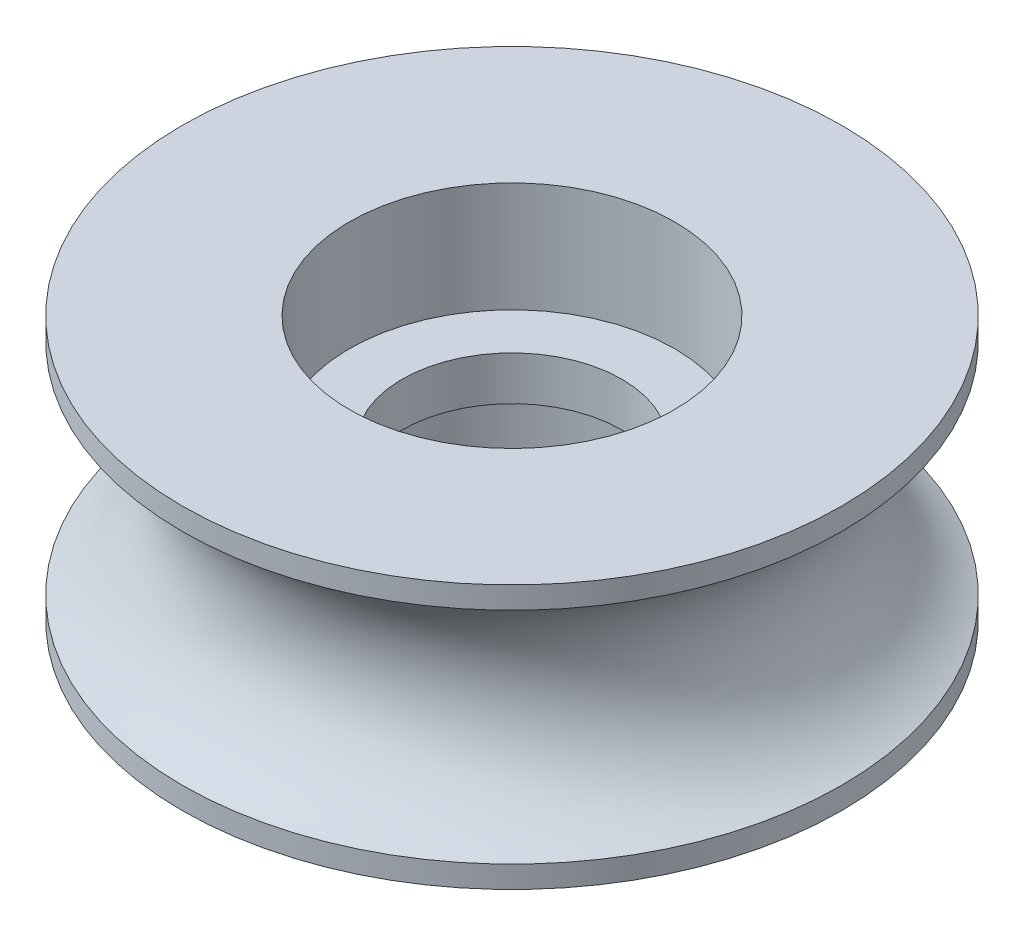
SolidWorks part; units mm, degrees
ref_plane "Ebene vorne" through (0, 0, 0) normal (0, 0, 1) x (1, 0, 0)
ref_plane "Ebene oben" through (0, 0, 0) normal (0, 1, 0) x (1, 0, 0)
ref_plane "Ebene rechts" through (0, 0, 0) normal (1, 0, 0) x (0, 0, -1)
sketch "Sketch1" plane through (0, 0, 0) normal (0, 0, 1) x (1, 0, 0)
  line L0 (0, -6.6295) -> (0, 11.8219) construction
  line L1 (-3.7, 0) -> (-7.5, 0)
  line L2 (-7.5, 0) -> (-7.5, 0.5)
  line L3 (-7.5, 6) -> (-3.7, 6)
  line L4 (-3.7, 6) -> (-3.7, 3.5)
  line L5 (-3.7, 2.5) -> (-3.7, 0)
  line L7 (-7.5, 5.5) -> (-7.5, 6)
  line L8 (-9.5865, 3) -> (-0.4874, 3) construction
  line L10 (-3.7, 2.5) -> (-2.5, 2.5)
  line L11 (-2.5, 2.5) -> (-2.5, 3.5)
  line L12 (-2.5, 3.5) -> (-3.7, 3.5)
  arc A1 (-7.5, 5.5) -> (-7.5, 0.5) centre (-8.5198, 3) cw
  dimension "D4" = 2.7
  dimension "D1" = 7.4
  dimension "D2" = 6
  dimension "D3" = 5
  dimension "D5" = 15
  dimension "D7" = 5
  dimension "D8" = 1
revolve "Revolve1" add sketch "Sketch1" angle 360 about L0
